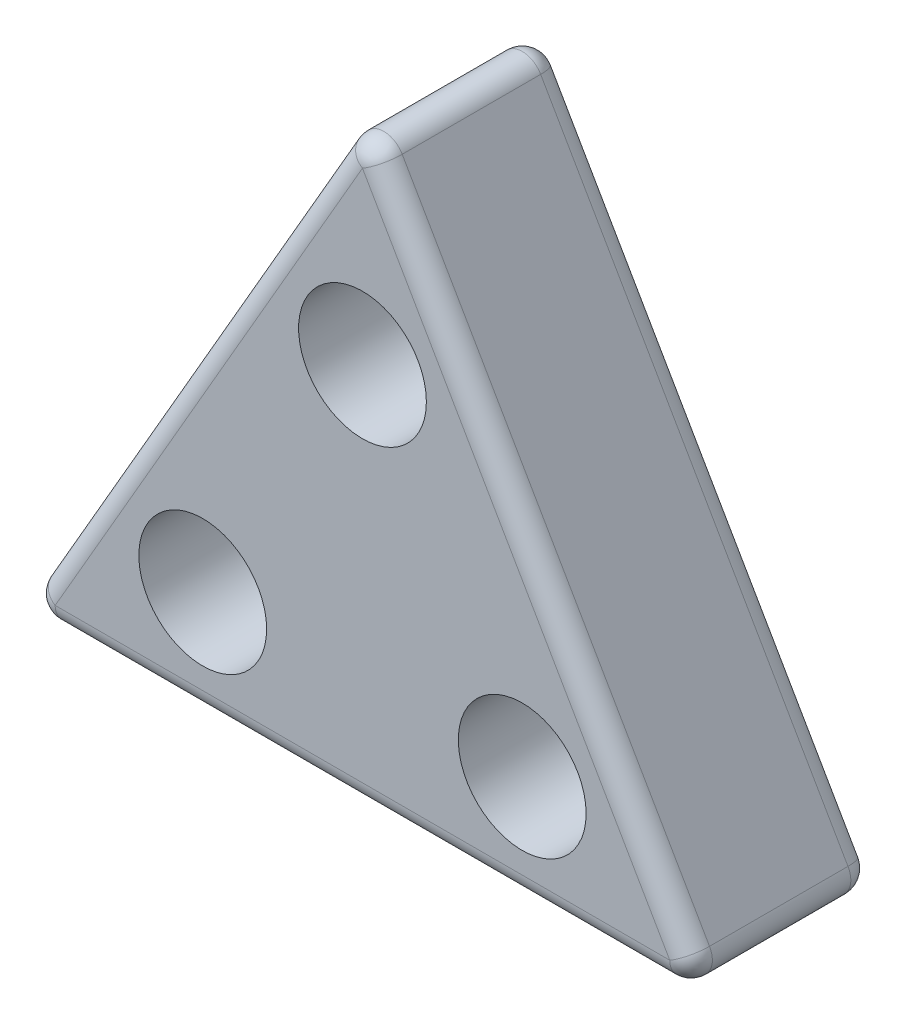
SolidWorks part; units mm, degrees
ref_plane "Plan de face" through (0, 0, 0) normal (0, 0, 1) x (1, 0, 0)
ref_plane "Plan de dessus" through (0, 0, 0) normal (0, 1, 0) x (1, 0, 0)
ref_plane "Plan de droite" through (0, 0, 0) normal (1, 0, 0) x (0, 0, -1)
sketch "Esquisse1" plane through (0, 0, 0) normal (0, 0, 1) x (1, 0, 0)
  line L0 (-7.5, 0) -> (7.5, 0) construction
  line L1 (0, 0) -> (0, 3.0572) construction
  line L2 (-7.5, 0) -> (0, 12.9904) construction
  line L3 (0, 12.9904) -> (7.5, 0) construction
  line L4 (0.866, 21.4904) -> (15.2942, -3.5)
  line L5 (-14.4282, -5) -> (14.4282, -5)
  line L6 (-15.2942, -3.5) -> (-0.866, 21.4904)
  line L7 (-16.1603, -5) -> (0, 22.9904) construction
  line L8 (0, 22.9904) -> (16.1603, -5) construction
  line L9 (-16.1603, -5) -> (16.1603, -5) construction
  circle A0 centre (-7.5, 0) radius 3
  circle A1 centre (7.5, 0) radius 3
  circle A2 centre (0, 12.9904) radius 3
  arc A3 (-0.866, 21.4904) -> (0.866, 21.4904) centre (0, 20.9904) cw
  arc A4 (15.2942, -3.5) -> (14.4282, -5) centre (14.4282, -4) cw
  arc A5 (-14.4282, -5) -> (-15.2942, -3.5) centre (-14.4282, -4) cw
  point P4 (0, 0)
  dimension "D1" = 6
  dimension "D2" = 6
  dimension "D5" = 6
  dimension "D7" = 1
  dimension "D3" = 15
  dimension "D4" = 60
  dimension "D6" = 5
extrude "Boss.-Extru.1" add sketch "Esquisse1" along normal blind 8.5
fillet "Congé1" radius 1 12 edges at (15.2942, -4.5, 0) (0, -5, 0) (-15.2942, -4.5, 0) (-8.0801, 8.9952, 0) (0, 21.9904, 0) (15.2942, -4.5, 8.5) (0, -5, 8.5) (-15.2942, -4.5, 8.5) (-8.0801, 8.9952, 8.5) (0, 21.9904, 8.5) (8.0801, 8.9952, 0) (8.0801, 8.9952, 8.5)
